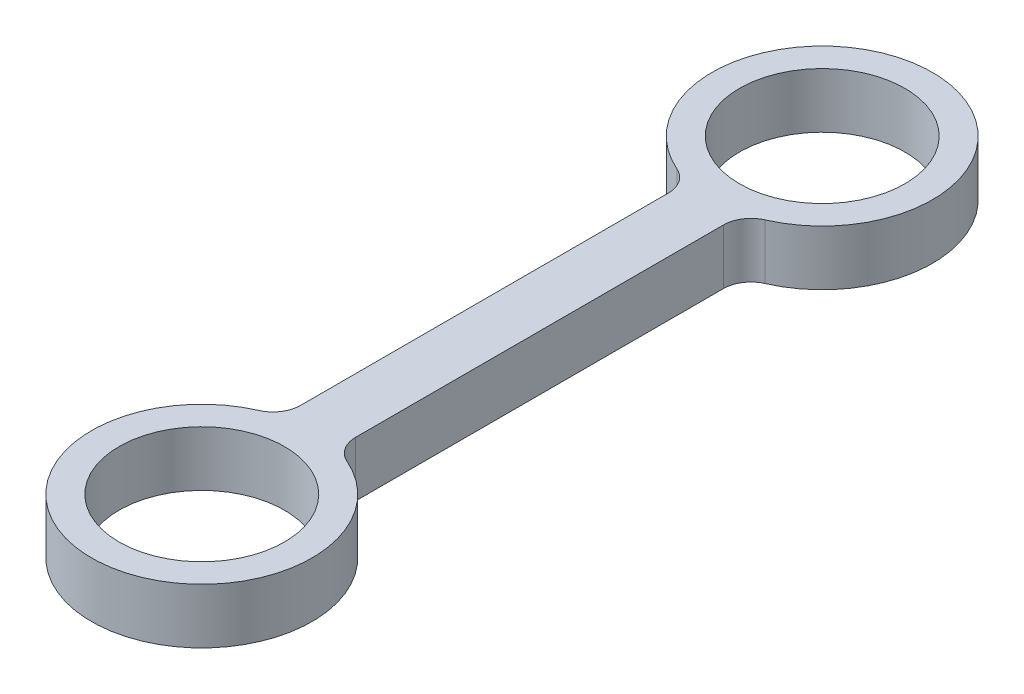
SolidWorks part; units mm, degrees
ref_plane "Front Plane" through (0, 0, 0) normal (0, 0, 1) x (1, 0, 0)
ref_plane "Top Plane" through (0, 0, 0) normal (0, 1, 0) x (1, 0, 0)
ref_plane "Right Plane" through (0, 0, 0) normal (1, 0, 0) x (0, 0, -1)
sketch "Sketch1" plane through (0, 0, 0) normal (0, 1, 0) x (1, 0, 0)
  line L0 (0, -11.25) -> (0, 11.25) construction
  line L1 (0, 0) -> (50000, 0) construction
  line L2 (-1, -7.377) -> (-1, 7.377)
  line L3 (1, -7.377) -> (1, 7.377)
  circle A0 centre (0, 11.25) radius 3
  circle A1 centre (0, 11.25) radius 4
  circle A2 centre (0, -11.25) radius 4
  circle A3 centre (0, -11.25) radius 3
  point P4 (0, 0)
  point P12 (-0.7077, 0)
  point P16 (1, 0)
  point P17 (-1, 0)
  point P21 (-1, -7.377)
  point P22 (1, -7.377)
  point P23 (-1, 7.377)
  dimension "D3" = 6
  dimension "D1" = 22.5
  dimension "D4" = 2
  dimension "D2" = 1
extrude "Boss-Extrude1" add sketch "Sketch1" along normal blind 2 contours A1 A0 | L2 A2 L3 A1 | A2 A3
fillet "Fillet1" radius 1 4 edges at (-1, 1, 7.377) (1, 1, 7.377) (1, 1, -7.377) (-1, 1, -7.377)
